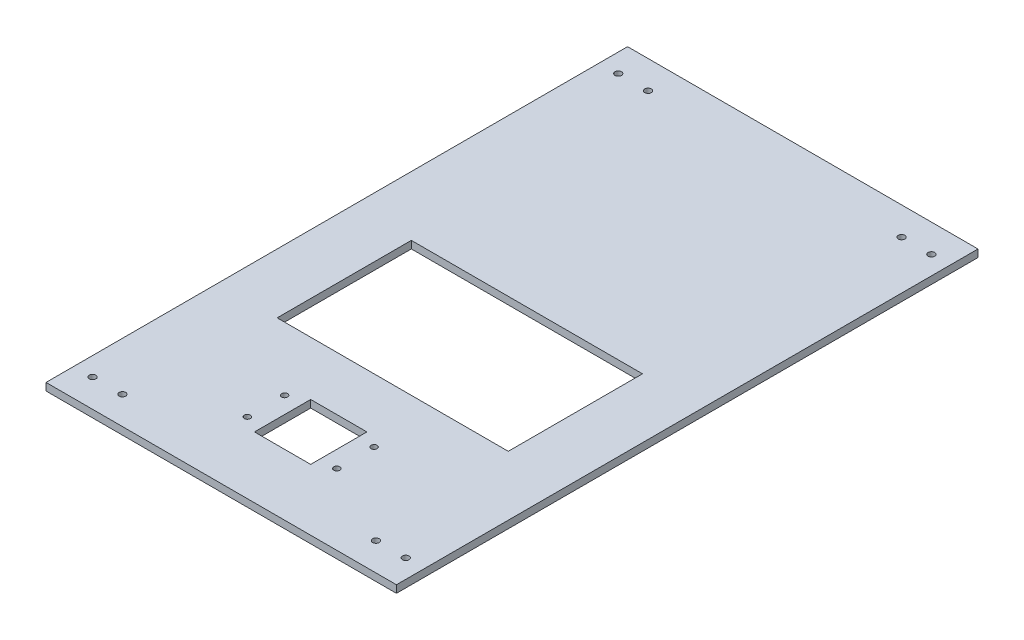
SolidWorks part; units mm, degrees
material "Acrylic (Medium-high impact)"
ref_plane "Front Plane" through (0, 0, 0) normal (0, 0, 1) x (1, 0, 0)
ref_plane "Top Plane" through (0, 0, 0) normal (0, 1, 0) x (1, 0, 0)
ref_plane "Right Plane" through (0, 0, 0) normal (1, 0, 0) x (0, 0, -1)
sketch "Sketch1" plane through (0, 0, 0) normal (0, 1, 0) x (1, 0, 0)
  line L1 (-149.225, -247.65) -> (149.225, -247.65)
  line L2 (-149.225, -247.65) -> (-149.225, 247.65)
  line L3 (-149.225, 247.65) -> (149.225, 247.65)
  line L4 (149.225, -247.65) -> (149.225, 247.65)
  line L5 (-149.225, -247.65) -> (149.225, 247.65) construction
  line L6 (-149.225, 247.65) -> (149.225, -247.65) construction
  line L7 (73.025, -247.65) -> (-130.175, -247.65)
  line L11 (-384.175, -247.65) -> (-231.775, -247.65)
  point P0 (0, 0)
  dimension "D1" = 298.45
  dimension "D2" = 495.3
extrude "Boss-Extrude1" add sketch "Sketch1" along normal mid plane 6.35 contours L1 L4 L3 L2
sketch "Sketch2" [suppressed] plane through (0, 0, 0) normal (0, 1, 0) x (1, 0, 0)
  line L0 (-247.65, -28.575) -> (247.65, -28.575) construction
  line L1 (158.75, -28.575) -> (63.5, -28.575)
  line L2 (158.75, -28.575) -> (158.75, -92.075)
  line L3 (158.75, -92.075) -> (63.5, -92.075)
  line L4 (63.5, -28.575) -> (63.5, -92.075)
  line L6 (-76.2, -28.575) -> (-165.1, -28.575)
  line L7 (-76.2, -28.575) -> (-76.2, -92.075)
  line L8 (-76.2, -92.075) -> (-165.1, -92.075)
  line L9 (-165.1, -28.575) -> (-165.1, -92.075)
  line L10 (247.65, -28.575) -> (247.65, 28.575) construction
  line L11 (-247.65, -28.575) -> (-247.65, 28.575) construction
  line L12 (-247.65, 28.575) -> (247.65, 28.575) construction
  line L13 (-247.65, -28.575) -> (-247.65, 28.575) construction
  point P19 (63.5, -92.075)
  dimension "D1" = 139.7
  dimension "D2" = 88.9
  dimension "D3" = 82.55
  dimension "D4" = 171.45
  dimension "D5" = 120.65
extrude "Boss-Extrude2" [suppressed] add sketch "Sketch2" along normal mid plane 6.35 contours L6 L9 L8 L7 | L2 L3 L4 L1
sketch "Sketch3" plane through (0, 3.175, 0) normal (0, 1, 0) x (1, 0, 0)
  line L0 (-149.225, 247.65) -> (149.225, 247.65) construction
  line L1 (-98.425, 12.7) -> (98.425, 12.7)
  line L2 (-98.425, 12.7) -> (-98.425, -101.6)
  line L3 (-98.425, -101.6) -> (98.425, -101.6)
  line L4 (98.425, 12.7) -> (98.425, -101.6)
  line L5 (-98.425, 12.7) -> (98.425, -101.6) construction
  line L6 (-98.425, -101.6) -> (98.425, 12.7) construction
  line L7 (-149.225, -247.65) -> (149.225, -247.65) construction
  point P0 (0, -44.45)
  point P7 (0, 247.65)
  point P8 (0, 12.7)
  dimension "D1" = 196.85
  dimension "D2" = 114.3
  dimension "D3" = 203.2
extrude "Cut-Extrude1" cut sketch "Sketch3" against normal through all and the other way through all
sketch "Sketch4" [suppressed] plane through (0, -3.175, 0) normal (0, -1, 0) x (1, 0, 0)
  line L0 (-107.315, 31.75) -> (107.315, 31.75) construction
  line L1 (-107.315, 33.9979) -> (107.315, 33.9979)
  line L2 (-107.315, 29.5021) -> (107.315, 29.5021)
  line L3 (-107.315, 6.35) -> (107.315, 6.35) construction
  line L4 (-107.315, 8.5979) -> (107.315, 8.5979)
  line L5 (-107.315, 4.1021) -> (107.315, 4.1021)
  arc A0 (-107.315, 33.9979) -> (-107.315, 29.5021) centre (-107.315, 31.75) ccw
  arc A1 (107.315, 29.5021) -> (107.315, 33.9979) centre (107.315, 31.75) ccw
  arc A2 (-107.315, 8.5979) -> (-107.315, 4.1021) centre (-107.315, 6.35) ccw
  arc A3 (107.315, 4.1021) -> (107.315, 8.5979) centre (107.315, 6.35) ccw
  point P0 (-107.315, 31.75)
  point P1 (107.315, 31.75)
  point P3 (107.315, 6.35)
  point P5 (-107.315, 6.35)
  point P10 (0, 31.75)
  point P15 (0, 6.35)
  dimension "D1" = 4.4958
  dimension "D2" = 4.4958
extrude "Cut-Extrude2" [suppressed] cut sketch "Sketch4" against normal through all
sketch "Sketch5" [suppressed] plane through (0, -3.175, 0) normal (0, -1, 0) x (1, 0, 0)
  line L0 (73.025, 79.375) -> (73.025, -9.525) construction
  line L1 (63.5, 28.575) -> (63.5, 92.075) construction
  line L2 (158.75, 92.075) -> (63.5, 92.075) construction
  line L3 (-247.65, -22.225) -> (247.65, -22.225) construction
  line L4 (73.025, 79.375) -> (73.025, -9.525) construction
  line L5 (75.2729, 79.375) -> (75.2729, -9.525)
  line L6 (70.7771, 79.375) -> (70.7771, -9.525)
  line L7 (-85.725, 79.375) -> (-85.725, -9.525) construction
  line L8 (-76.2, 28.575) -> (-76.2, 92.075) construction
  line L9 (-76.2, 92.075) -> (-165.1, 92.075) construction
  line L10 (-85.725, 79.375) -> (-85.725, -9.525) construction
  line L11 (-83.4771, 79.375) -> (-83.4771, -9.525)
  line L12 (-87.9729, 79.375) -> (-87.9729, -9.525)
  arc A0 (75.2729, 79.375) -> (70.7771, 79.375) centre (73.025, 79.375) ccw
  arc A1 (70.7771, -9.525) -> (75.2729, -9.525) centre (73.025, -9.525) ccw
  arc A2 (-83.4771, 79.375) -> (-87.9729, 79.375) centre (-85.725, 79.375) ccw
  arc A3 (-87.9729, -9.525) -> (-83.4771, -9.525) centre (-85.725, -9.525) ccw
  point P8 (73.025, 34.925)
  point P19 (-85.725, 34.925)
  dimension "D1" = 9.525
  dimension "D2" = 12.7
  dimension "D3" = 12.7
  dimension "D4" = 4.4958
  dimension "D5" = 9.525
  dimension "D6" = 12.7
  dimension "D7" = 12.7
  dimension "D8" = 4.4958
extrude "Cut-Extrude3" [suppressed] cut sketch "Sketch5" against normal through all contours L12 A3 L11 A2 | L6 A1 L5 A0
sketch "Sketch6" [suppressed] plane through (0, 3.175, 0) normal (0, 1, 0) x (1, 0, 0)
  line L0 (-79.375, -38.1) -> (-79.375, 38.1) construction
  line L1 (-88.9, -50.8) -> (-88.9, 50.8) construction
  line L2 (-88.9, -50.8) -> (88.9, -50.8) construction
  line L3 (-88.9, 50.8) -> (88.9, 50.8) construction
  line L4 (79.375, -38.1) -> (79.375, 38.1) construction
  line L5 (88.9, -50.8) -> (88.9, 50.8) construction
  line L6 (-79.375, -38.1) -> (-79.375, 38.1) construction
  line L7 (-81.6229, -38.1) -> (-81.6229, 38.1)
  line L8 (-77.1271, -38.1) -> (-77.1271, 38.1)
  line L9 (79.375, -38.1) -> (79.375, 38.1) construction
  line L10 (77.1271, -38.1) -> (77.1271, 38.1)
  line L11 (81.6229, -38.1) -> (81.6229, 38.1)
  arc A0 (-81.6229, -38.1) -> (-77.1271, -38.1) centre (-79.375, -38.1) ccw
  arc A1 (-77.1271, 38.1) -> (-81.6229, 38.1) centre (-79.375, 38.1) ccw
  arc A2 (77.1271, -38.1) -> (81.6229, -38.1) centre (79.375, -38.1) ccw
  arc A3 (81.6229, 38.1) -> (77.1271, 38.1) centre (79.375, 38.1) ccw
  point P12 (-79.375, 0)
  point P17 (79.375, 0)
  dimension "D1" = 9.525
  dimension "D2" = 12.7
  dimension "D3" = 12.7
  dimension "D4" = 9.525
  dimension "D5" = 12.7
  dimension "D6" = 12.7
  dimension "D7" = 4.4958
  dimension "D8" = 4.4958
extrude "Cut-Extrude4" [suppressed] cut sketch "Sketch6" against normal through all
sketch "Sketch7" [suppressed] plane through (0, 3.175, 0) normal (0, 1, 0) x (1, 0, 0)
  point P0 (115.1313, 66.802)
  point P1 (139.827, 42.1063)
  point P3 (-139.827, 42.1063)
  point P5 (-115.1313, 66.802)
hole_wizard "#12 Clearance Hole1" [suppressed] positions "Sketch8" profile "Sketch9" hole size "#12" standard "ANSI Inch"
sketch "Sketch8" plane through (0, 3.175, 0) normal (0, 1, 0) x (1, 0, 0)
  point P0 (-139.827, 42.1063)
  point P3 (-115.1313, 66.802)
  point P6 (115.1313, 66.802)
  point P9 (139.827, 42.1063)
sketch "Sketch9" plane through (-139.827, 3.175, -42.1063) normal (1, 0, 0) x (0, 0, 1)
  line L0 (0, 0) -> (0, 18.1964)
  line L1 (0, 18.1964) -> (2.8067, 16.51)
  line L2 (2.8067, 16.51) -> (2.8067, 0)
  line L5 (2.8067, 0) -> (0, 0)
  line L10 (0, 18.1964) -> (-2.8067, 16.51) construction
  line L11 (0, -6.35) -> (0, 107.95) construction
  dimension "Hole Dia." = 5.6134
  dimension "Hole Depth" = 16.51
  dimension "Drill Angle" = 118
sketch "Sketch10" [suppressed] plane through (0, -3.175, 0) normal (0, -1, 0) x (1, 0, 0)
  point P0 (223.8375, -6.35)
  point P1 (223.8375, 19.05)
  point P3 (-223.8375, 19.05)
  point P5 (-223.8375, -6.35)
hole_wizard "#12 Clearance Hole3" [suppressed] positions "Sketch11" profile "Sketch12" hole size "#12" standard "ANSI Inch"
sketch "Sketch11" plane through (0, -3.175, 0) normal (0, -1, 0) x (-1, 0, 0)
  point P0 (-223.8375, -19.05)
  point P3 (-223.8375, 6.35)
  point P6 (223.8375, -19.05)
  point P9 (223.8375, 6.35)
sketch "Sketch12" plane through (223.8375, -3.175, 19.05) normal (1, 0, 0) x (0, 0, -1)
  line L0 (0, 0) -> (0, 18.1964)
  line L1 (0, 18.1964) -> (2.8067, 16.51)
  line L2 (2.8067, 16.51) -> (2.8067, 0)
  line L5 (2.8067, 0) -> (0, 0)
  line L10 (0, 18.1964) -> (-2.8067, 16.51) construction
  line L11 (0, -6.35) -> (0, 107.95) construction
  dimension "Hole Dia." = 5.6134
  dimension "Hole Depth" = 16.51
  dimension "Drill Angle" = 118
sketch "Sketch13" plane through (0, -3.175, 0) normal (0, -1, 0) x (1, 0, 0)
  point P0 (133.35, -223.8375)
  point P1 (107.95, -223.8375)
  point P3 (-107.95, -223.8375)
  point P5 (-133.35, -223.8375)
  point P7 (133.35, 223.8375)
  point P9 (107.95, 223.8375)
  point P11 (-107.95, 223.8375)
  point P13 (-133.35, 223.8375)
hole_wizard "#12 Clearance Hole2" positions "Sketch14" profile "Sketch15" hole size "#12" standard "ANSI Inch"
sketch "Sketch14" plane through (0, -3.175, 0) normal (0, -1, 0) x (-1, 0, 0)
  point P0 (107.95, -223.8375)
  point P3 (133.35, -223.8375)
  point P6 (133.35, 223.8375)
  point P9 (107.95, 223.8375)
  point P12 (-133.35, 223.8375)
  point P15 (-107.95, 223.8375)
  point P18 (-133.35, -223.8375)
  point P21 (-107.95, -223.8375)
sketch "Sketch15" plane through (-107.95, -3.175, 223.8375) normal (1, 0, 0) x (0, 0, -1)
  line L0 (0, 0) -> (0, 18.1964)
  line L1 (0, 18.1964) -> (2.8067, 16.51)
  line L2 (2.8067, 16.51) -> (2.8067, 0)
  line L5 (2.8067, 0) -> (0, 0)
  line L10 (0, 18.1964) -> (-2.8067, 16.51) construction
  line L11 (0, -6.35) -> (0, 107.95) construction
  dimension "Hole Dia." = 5.6134
  dimension "Hole Depth" = 16.51
  dimension "Drill Angle" = 118
sketch "Sketch16" [suppressed] plane through (0, 3.175, 0) normal (0, 1, 0) x (1, 0, 0)
  line L0 (88.9, -50.8) -> (88.9, 50.8) construction
  line L1 (-88.9, -50.8) -> (-88.9, 50.8) construction
  line L2 (-88.9, -50.8) -> (88.9, -50.8) construction
  point P0 (79.375, -38.1)
  point P1 (-79.375, -38.1)
  dimension "D1" = 9.525
  dimension "D2" = 9.525
  dimension "D3" = 12.7
hole_wizard "#8 Clearance Hole1" [suppressed] positions "Sketch17" profile "Sketch19" hole size "#8" standard "ANSI Inch"
sketch "Sketch17" plane through (0, 3.175, 0) normal (0, 1, 0) x (1, 0, 0)
  point P0 (79.375, -38.1)
  point P3 (-79.375, -38.1)
sketch "Sketch19" plane through (79.375, 3.175, 38.1) normal (1, 0, 0) x (0, 0, 1)
  line L0 (0, 0) -> (0, 12.0187)
  line L1 (0, 12.0187) -> (2.2479, 10.668)
  line L2 (2.2479, 10.668) -> (2.2479, 0)
  line L5 (2.2479, 0) -> (0, 0)
  line L10 (0, 12.0187) -> (-2.2479, 10.668) construction
  line L11 (0, -6.35) -> (0, 107.95) construction
  dimension "Hole Dia." = 4.4958
  dimension "Hole Depth" = 10.668
  dimension "Drill Angle" = 118
sketch "Sketch20" plane through (0, -3.175, 0) normal (0, -1, 0) x (1, 0, 0)
  line L0 (-149.225, 247.65) -> (149.225, 247.65) construction
  line L1 (23.9395, 147.5105) -> (-23.9395, 147.5105)
  line L2 (23.9395, 147.5105) -> (23.9395, 195.3895)
  line L3 (23.9395, 195.3895) -> (-23.9395, 195.3895)
  line L4 (-23.9395, 147.5105) -> (-23.9395, 195.3895)
  line L5 (23.9395, 147.5105) -> (-23.9395, 195.3895) construction
  line L6 (23.9395, 195.3895) -> (-23.9395, 147.5105) construction
  line L8 (38.1, 155.575) -> (-38.1, 155.575) construction
  line L9 (38.1, 155.575) -> (38.1, 187.325) construction
  line L10 (38.1, 187.325) -> (-38.1, 187.325) construction
  line L11 (-38.1, 155.575) -> (-38.1, 187.325) construction
  point P0 (0, 171.45)
  point P7 (0, 247.65)
  point P8 (38.1, 155.575)
  point P9 (38.1, 187.325)
  point P10 (-38.1, 155.575)
  point P11 (-38.1, 187.325)
  point P18 (0, 187.325)
  point P19 (0, 195.3895)
  point P20 (-38.1, 171.45)
  point P21 (-23.9395, 171.45)
  dimension "D1" = 47.879
  dimension "D2" = 47.879
  dimension "D3" = 38.1
  dimension "D4" = 15.875
  dimension "D5" = 76.2
extrude "Cut-Extrude5" cut sketch "Sketch20" against normal through all contours L1 L4 L3 L2
hole_wizard "#10 Clearance Hole1" positions "Sketch21" profile "Sketch22" hole size "#10" standard "ANSI Inch"
sketch "Sketch21" plane through (0, -3.175, 0) normal (0, -1, 0) x (-1, 0, 0)
  point P0 (-38.1, -155.575)
  point P3 (38.1, -155.575)
  point P6 (38.1, -187.325)
  point P9 (-38.1, -187.325)
sketch "Sketch22" plane through (38.1, -3.175, 155.575) normal (1, 0, 0) x (0, 0, -1)
  line L0 (0, 0) -> (0, 12.2018)
  line L1 (0, 12.2018) -> (2.5527, 10.668)
  line L2 (2.5527, 10.668) -> (2.5527, 0)
  line L5 (2.5527, 0) -> (0, 0)
  line L10 (0, 12.2018) -> (-2.5527, 10.668) construction
  line L11 (0, -6.35) -> (0, 107.95) construction
  dimension "Hole Dia." = 5.1054
  dimension "Hole Depth" = 10.668
  dimension "Drill Angle" = 118
